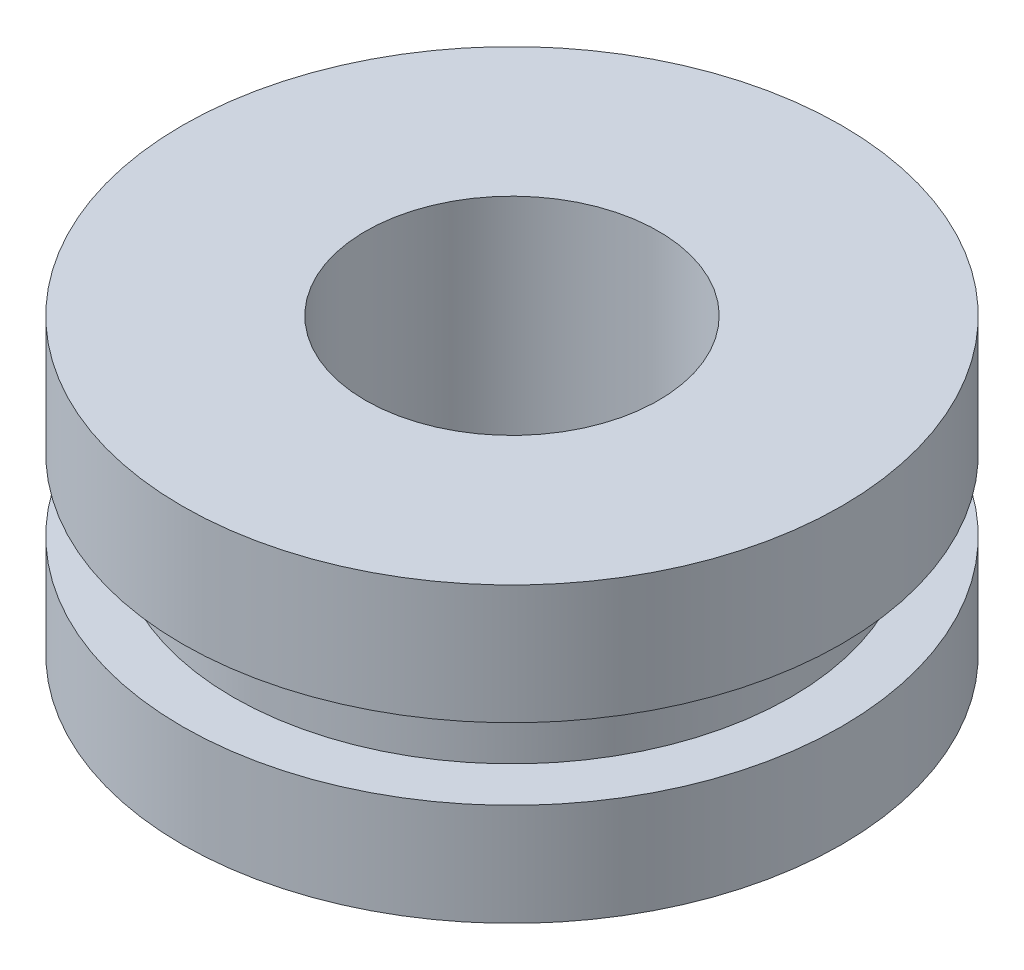
SolidWorks part; units mm, degrees
ref_plane "前视基准面" through (0, 0, 0) normal (0, 0, 1) x (1, 0, 0)
ref_plane "上视基准面" through (0, 0, 0) normal (0, 1, 0) x (1, 0, 0)
ref_plane "右视基准面" through (0, 0, 0) normal (1, 0, 0) x (0, 0, -1)
sketch "草图1" plane through (0, 0, 0) normal (0, 1, 0) x (1, 0, 0)
  circle A0 centre (0, 0) radius 2
  circle A1 centre (0, 0) radius 4.5
  dimension "D1" = 4
  dimension "D2" = 9
extrude "凸台-拉伸1" add sketch "草图1" along normal blind 4
sketch "草图2" plane through (0, 0, 0) normal (0, 0, 1) x (1, 0, 0)
  line L0 (-4.5, 2.3713) -> (-3.8068, 2.3713)
  line L1 (-4.5, 4) -> (-4.5, 0) construction
  line L2 (-3.8068, 2.3713) -> (-3.8068, 1.3954)
  line L3 (-3.8068, 1.3954) -> (-4.5, 1.3954)
  line L4 (-4.5, 1.3954) -> (-4.5, 2.3713)
ref_axis "基准轴1" through (0, 4, 0) along (0, -1, 0)
revolve "切除-旋转1" cut sketch "草图2" angle 360 about axis through (0, 4, 0) along (0, -1, 0)
